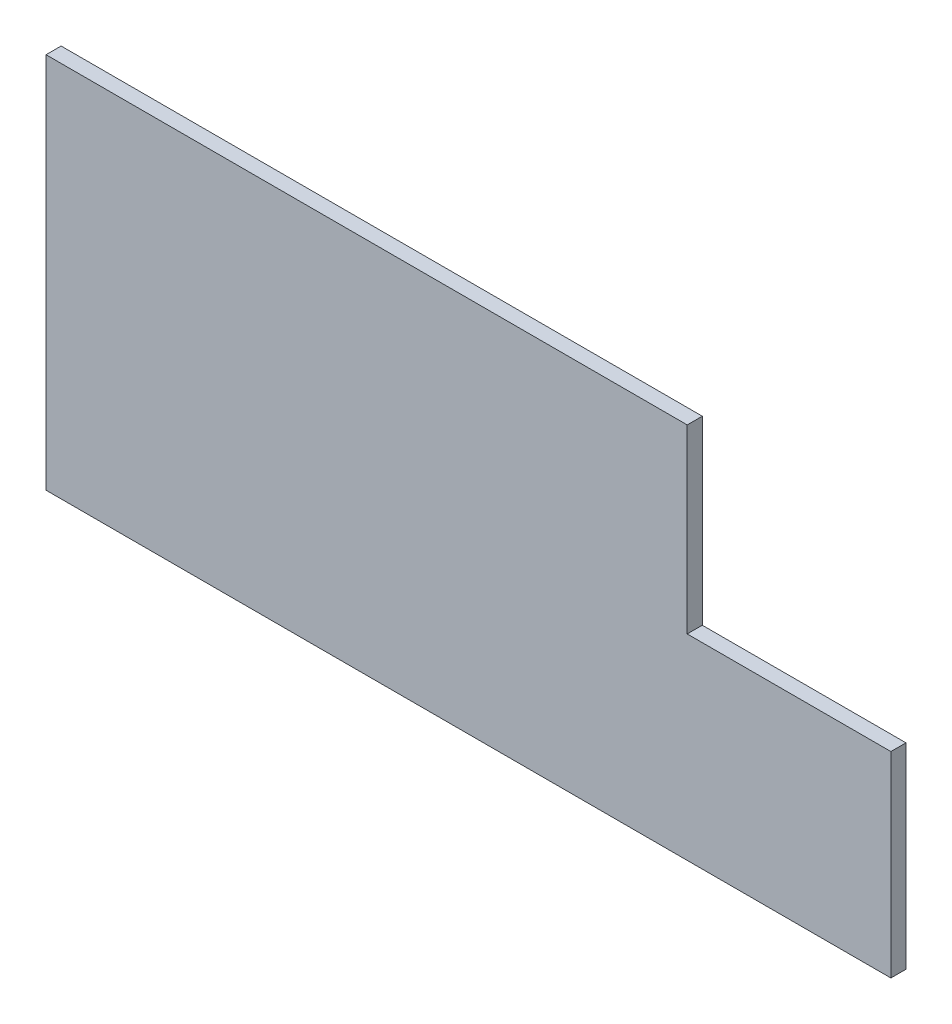
SolidWorks part; units mm, degrees
ref_plane "Plan de face" through (0, 0, 0) normal (0, 0, 1) x (1, 0, 0)
ref_plane "Plan de dessus" through (0, 0, 0) normal (0, 1, 0) x (1, 0, 0)
ref_plane "Plan de droite" through (0, 0, 0) normal (1, 0, 0) x (0, 0, -1)
sketch "Esquisse1" plane through (0, 0, 0) normal (0, 0, 1) x (1, 0, 0)
  line L1 (-103.5883, 48.6413) -> (66.4117, 48.6413)
  line L2 (-103.5883, 48.6413) -> (-103.5883, -51.3587)
  line L3 (-103.5883, -51.3587) -> (66.4117, -51.3587)
  line L4 (66.4117, 48.6413) -> (66.4117, -51.3587)
  dimension "D1" = 100
  dimension "D2" = 170
extrude "Boss.-Extru.1" add sketch "Esquisse1" along normal blind 4
sketch "Esquisse2" plane through (66.4117, 0, 0) normal (1, 0, 0) x (0, 0, -1)
  line L0 (0, -51.3587) -> (0, 48.6413) construction
  line L1 (-4, 0.6413) -> (0, 0.6413)
  line L2 (-4, 0.6413) -> (-4, -51.3587)
  line L3 (-4, -51.3587) -> (0, -51.3587)
  line L4 (0, 0.6413) -> (0, -51.3587)
  line L5 (-4, -51.3587) -> (0, -51.3587) construction
  line L6 (-4, -51.3587) -> (-4, 48.6413) construction
  dimension "D1" = 52
extrude "Boss.-Extru.2" add sketch "Esquisse2" along normal blind 54
